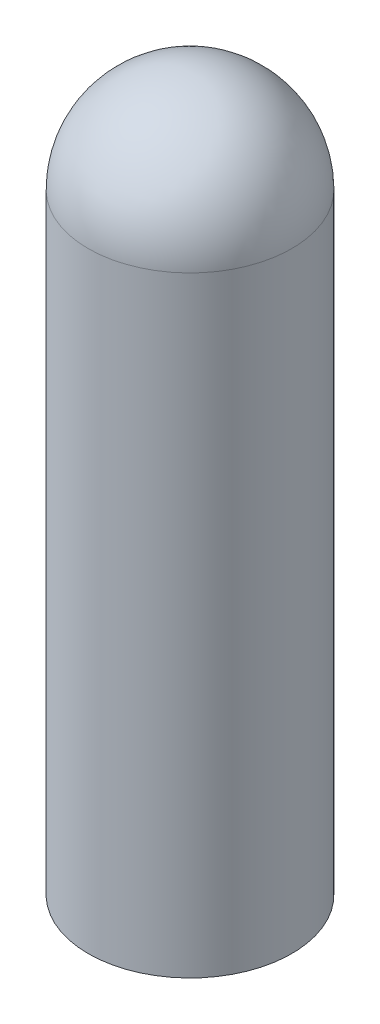
SolidWorks part; units mm, degrees
ref_plane "Front Plane" through (0, 0, 0) normal (0, 0, 1) x (1, 0, 0)
ref_plane "Top Plane" through (0, 0, 0) normal (0, 1, 0) x (1, 0, 0)
ref_plane "Right Plane" through (0, 0, 0) normal (1, 0, 0) x (0, 0, -1)
sketch "Sketch1" plane through (0, 0, 0) normal (0, 1, 0) x (1, 0, 0)
  circle A0 centre (0, 0) radius 25.4
extrude "Boss-Extrude1" add sketch "Sketch1" along normal blind 152.4
sketch "Sketch2" plane through (0, 152.4, 0) normal (0, 1, 0) x (1, 0, 0)
  line L0 (0, 25.4) -> (0, -25.4)
  arc A0 (0, 25.4) -> (0, -25.4) centre (0, 0) ccw
revolve "Revolve1" add sketch "Sketch2" angle 360 about L0
sketch "Sketch4" plane through (0, 0, 0) normal (0, -1, 0) x (1, 0, 0)
  circle A0 centre (0, 0) radius 6.35
extrude "Cut-Extrude1" cut sketch "Sketch4" against normal blind 175.26
